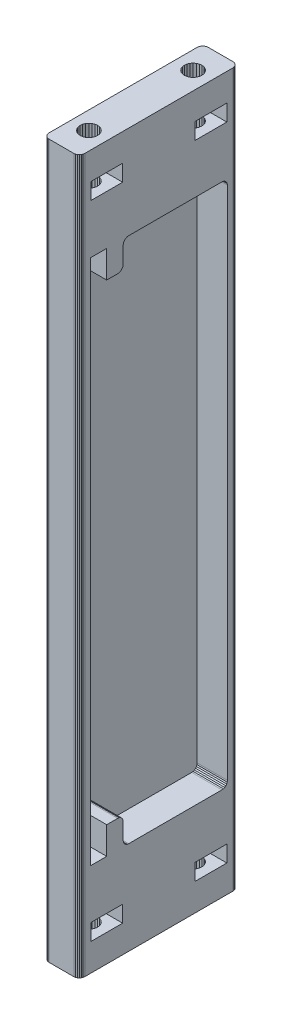
SolidWorks part; units mm, degrees
ref_plane "Front Plane" through (0, 0, 0) normal (0, 0, 1) x (1, 0, 0)
ref_plane "Top Plane" through (0, 0, 0) normal (0, 1, 0) x (1, 0, 0)
ref_plane "Right Plane" through (0, 0, 0) normal (1, 0, 0) x (0, 0, -1)
ref_plane "Plane1" through (0, 130, 0) normal (0, 1, 0) x (1, 0, 0)
sketch "Sketch1" plane through (0, 130, 0) normal (0, 1, 0) x (1, 0, 0)
  line L0 (-2.75, 35.134) -> (-2.5088, 35.0341)
  line L1 (-2.5088, 35.0341) -> (-2.25, 35)
  line L2 (-2.25, 35) -> (2.25, 35)
  line L3 (2.25, 35) -> (2.5088, 35.0341)
  line L4 (2.5088, 35.0341) -> (2.75, 35.134)
  line L5 (2.75, 35.134) -> (2.9571, 35.2929)
  line L6 (2.9571, 35.2929) -> (3.116, 35.5)
  line L7 (3.116, 35.5) -> (3.2159, 35.7412)
  line L8 (3.2159, 35.7412) -> (3.25, 36)
  line L9 (3.25, 36) -> (3.25, 63)
  line L10 (3.25, 63) -> (3.2159, 63.2588)
  line L11 (3.2159, 63.2588) -> (3.116, 63.5)
  line L12 (3.116, 63.5) -> (2.9571, 63.7071)
  line L13 (2.9571, 63.7071) -> (2.75, 63.866)
  line L14 (2.75, 63.866) -> (2.5088, 63.9659)
  line L15 (2.5088, 63.9659) -> (2.25, 64)
  line L16 (2.25, 64) -> (-2.25, 64)
  line L17 (-2.25, 64) -> (-2.5088, 63.9659)
  line L18 (-2.5088, 63.9659) -> (-2.75, 63.866)
  line L19 (-2.75, 63.866) -> (-2.9571, 63.7071)
  line L20 (-2.9571, 63.7071) -> (-3.116, 63.5)
  line L21 (-3.116, 63.5) -> (-3.2159, 63.2588)
  line L22 (-3.2159, 63.2588) -> (-3.25, 63)
  line L23 (-3.25, 63) -> (-3.25, 36)
  line L24 (-3.25, 36) -> (-3.2159, 35.7412)
  line L25 (-3.2159, 35.7412) -> (-3.116, 35.5)
  line L26 (-3.116, 35.5) -> (-2.9571, 35.2929)
  line L27 (-2.9571, 35.2929) -> (-2.75, 35.134)
extrude "Boss-Extrude1" add sketch "Sketch1" against normal blind 130
sketch "Sketch2" plane through (3.25, 0, 0) normal (1, 0, 0) x (0, 0, -1)
  line L0 (37.1, 8) -> (37.1, 5)
  line L1 (37.1, 5) -> (42.9, 5)
  line L2 (42.9, 5) -> (42.9, 8)
  line L3 (42.9, 8) -> (37.1, 8)
extrude "Cut-Extrude1" cut sketch "Sketch2" against normal through all
sketch "Sketch3" plane through (0, 0, 0) normal (0, -1, 0) x (1, 0, 0)
  line L0 (-1.5455, -40.4141) -> (-1.3856, -40.8)
  line L1 (-1.3856, -40.8) -> (-1.1314, -41.1314)
  line L2 (-1.1314, -41.1314) -> (-0.8, -41.3856)
  line L3 (-0.8, -41.3856) -> (-0.4141, -41.5455)
  line L4 (-0.4141, -41.5455) -> (0, -41.6)
  line L5 (0, -41.6) -> (0.4141, -41.5455)
  line L6 (0.4141, -41.5455) -> (0.8, -41.3856)
  line L7 (0.8, -41.3856) -> (1.1314, -41.1314)
  line L8 (1.1314, -41.1314) -> (1.3856, -40.8)
  line L9 (1.3856, -40.8) -> (1.5455, -40.4141)
  line L10 (1.5455, -40.4141) -> (1.6, -40)
  line L11 (1.6, -40) -> (1.5455, -39.5859)
  line L12 (1.5455, -39.5859) -> (1.3856, -39.2)
  line L13 (1.3856, -39.2) -> (1.1314, -38.8686)
  line L14 (1.1314, -38.8686) -> (0.8, -38.6144)
  line L15 (0.8, -38.6144) -> (0.4141, -38.4545)
  line L16 (0.4141, -38.4545) -> (0, -38.4)
  line L17 (0, -38.4) -> (-0.4141, -38.4545)
  line L18 (-0.4141, -38.4545) -> (-0.8, -38.6144)
  line L19 (-0.8, -38.6144) -> (-1.1314, -38.8686)
  line L20 (-1.1314, -38.8686) -> (-1.3856, -39.2)
  line L21 (-1.3856, -39.2) -> (-1.5455, -39.5859)
  line L22 (-1.5455, -39.5859) -> (-1.6, -40)
  line L23 (-1.6, -40) -> (-1.5455, -40.4141)
extrude "Cut-Extrude2" cut sketch "Sketch3" against normal up to next
sketch "Sketch4" plane through (3.25, 0, 0) normal (1, 0, 0) x (0, 0, -1)
  line L0 (37.1, 125) -> (37.1, 122)
  line L1 (37.1, 122) -> (42.9, 122)
  line L2 (42.9, 122) -> (42.9, 125)
  line L3 (42.9, 125) -> (37.1, 125)
extrude "Cut-Extrude3" cut sketch "Sketch4" against normal through all
sketch "Sketch5" plane through (3.25, 0, 0) normal (1, 0, 0) x (0, 0, -1)
  line L0 (61.9, 125) -> (56.1, 125)
  line L1 (56.1, 125) -> (56.1, 122)
  line L2 (56.1, 122) -> (61.9, 122)
  line L3 (61.9, 122) -> (61.9, 125)
extrude "Cut-Extrude4" cut sketch "Sketch5" against normal through all
sketch "Sketch6" plane through (0, 130, 0) normal (0, 1, 0) x (-1, 0, 0)
  line L0 (1.5455, -39.5859) -> (1.3856, -39.2)
  line L1 (1.3856, -39.2) -> (1.1314, -38.8686)
  line L2 (1.1314, -38.8686) -> (0.8, -38.6144)
  line L3 (0.8, -38.6144) -> (0.4141, -38.4545)
  line L4 (0.4141, -38.4545) -> (0, -38.4)
  line L5 (0, -38.4) -> (-0.4141, -38.4545)
  line L6 (-0.4141, -38.4545) -> (-0.8, -38.6144)
  line L7 (-0.8, -38.6144) -> (-1.1314, -38.8686)
  line L8 (-1.1314, -38.8686) -> (-1.3856, -39.2)
  line L9 (-1.3856, -39.2) -> (-1.5455, -39.5859)
  line L10 (-1.5455, -39.5859) -> (-1.6, -40)
  line L11 (-1.6, -40) -> (-1.5455, -40.4141)
  line L12 (-1.5455, -40.4141) -> (-1.3856, -40.8)
  line L13 (-1.3856, -40.8) -> (-1.1314, -41.1314)
  line L14 (-1.1314, -41.1314) -> (-0.8, -41.3856)
  line L15 (-0.8, -41.3856) -> (-0.4141, -41.5455)
  line L16 (-0.4141, -41.5455) -> (0, -41.6)
  line L17 (0, -41.6) -> (0.4141, -41.5455)
  line L18 (0.4141, -41.5455) -> (0.8, -41.3856)
  line L19 (0.8, -41.3856) -> (1.1314, -41.1314)
  line L20 (1.1314, -41.1314) -> (1.3856, -40.8)
  line L21 (1.3856, -40.8) -> (1.5455, -40.4141)
  line L22 (1.5455, -40.4141) -> (1.6, -40)
  line L23 (1.6, -40) -> (1.5455, -39.5859)
extrude "Cut-Extrude5" cut sketch "Sketch6" against normal up to next
sketch "Sketch7" plane through (0, 130, 0) normal (0, 1, 0) x (-1, 0, 0)
  line L0 (-1.6, -59) -> (-1.5455, -59.4141)
  line L1 (-1.5455, -59.4141) -> (-1.3856, -59.8)
  line L2 (-1.3856, -59.8) -> (-1.1314, -60.1314)
  line L3 (-1.1314, -60.1314) -> (-0.8, -60.3856)
  line L4 (-0.8, -60.3856) -> (-0.4141, -60.5455)
  line L5 (-0.4141, -60.5455) -> (0, -60.6)
  line L6 (0, -60.6) -> (0.4141, -60.5455)
  line L7 (0.4141, -60.5455) -> (0.8, -60.3856)
  line L8 (0.8, -60.3856) -> (1.1314, -60.1314)
  line L9 (1.1314, -60.1314) -> (1.3856, -59.8)
  line L10 (1.3856, -59.8) -> (1.5455, -59.4141)
  line L11 (1.5455, -59.4141) -> (1.6, -59)
  line L12 (1.6, -59) -> (1.5455, -58.5859)
  line L13 (1.5455, -58.5859) -> (1.3856, -58.2)
  line L14 (1.3856, -58.2) -> (1.1314, -57.8686)
  line L15 (1.1314, -57.8686) -> (0.8, -57.6144)
  line L16 (0.8, -57.6144) -> (0.4141, -57.4545)
  line L17 (0.4141, -57.4545) -> (0, -57.4)
  line L18 (0, -57.4) -> (-0.4141, -57.4545)
  line L19 (-0.4141, -57.4545) -> (-0.8, -57.6144)
  line L20 (-0.8, -57.6144) -> (-1.1314, -57.8686)
  line L21 (-1.1314, -57.8686) -> (-1.3856, -58.2)
  line L22 (-1.3856, -58.2) -> (-1.5455, -58.5859)
  line L23 (-1.5455, -58.5859) -> (-1.6, -59)
extrude "Cut-Extrude6" cut sketch "Sketch7" against normal up to next
sketch "Sketch8" plane through (3.25, 0, 0) normal (1, 0, 0) x (0, 0, -1)
  line L0 (56.1, 8) -> (56.1, 5)
  line L1 (56.1, 5) -> (61.9, 5)
  line L2 (61.9, 5) -> (61.9, 8)
  line L3 (61.9, 8) -> (56.1, 8)
extrude "Cut-Extrude7" cut sketch "Sketch8" against normal through all
sketch "Sketch9" plane through (0, 0, 0) normal (0, -1, 0) x (1, 0, 0)
  line L0 (-0.8, -57.6144) -> (-1.1314, -57.8686)
  line L1 (-1.1314, -57.8686) -> (-1.3856, -58.2)
  line L2 (-1.3856, -58.2) -> (-1.5455, -58.5859)
  line L3 (-1.5455, -58.5859) -> (-1.6, -59)
  line L4 (-1.6, -59) -> (-1.5455, -59.4141)
  line L5 (-1.5455, -59.4141) -> (-1.3856, -59.8)
  line L6 (-1.3856, -59.8) -> (-1.1314, -60.1314)
  line L7 (-1.1314, -60.1314) -> (-0.8, -60.3856)
  line L8 (-0.8, -60.3856) -> (-0.4141, -60.5455)
  line L9 (-0.4141, -60.5455) -> (0, -60.6)
  line L10 (0, -60.6) -> (0.4141, -60.5455)
  line L11 (0.4141, -60.5455) -> (0.8, -60.3856)
  line L12 (0.8, -60.3856) -> (1.1314, -60.1314)
  line L13 (1.1314, -60.1314) -> (1.3856, -59.8)
  line L14 (1.3856, -59.8) -> (1.5455, -59.4141)
  line L15 (1.5455, -59.4141) -> (1.6, -59)
  line L16 (1.6, -59) -> (1.5455, -58.5859)
  line L17 (1.5455, -58.5859) -> (1.3856, -58.2)
  line L18 (1.3856, -58.2) -> (1.1314, -57.8686)
  line L19 (1.1314, -57.8686) -> (0.8, -57.6144)
  line L20 (0.8, -57.6144) -> (0.4141, -57.4545)
  line L21 (0.4141, -57.4545) -> (0, -57.4)
  line L22 (0, -57.4) -> (-0.4141, -57.4545)
  line L23 (-0.4141, -57.4545) -> (-0.8, -57.6144)
extrude "Cut-Extrude8" cut sketch "Sketch9" against normal up to next
sketch "Sketch10" plane through (3.25, 0, 0) normal (1, 0, 0) x (0, 0, -1)
  line L0 (62, 18) -> (62, 112)
  line L1 (62, 112) -> (61.9659, 112.2588)
  line L2 (61.9659, 112.2588) -> (61.866, 112.5)
  line L3 (61.866, 112.5) -> (61.7071, 112.7071)
  line L4 (61.7071, 112.7071) -> (61.5, 112.866)
  line L5 (61.5, 112.866) -> (61.2588, 112.9659)
  line L6 (61.2588, 112.9659) -> (61, 113)
  line L7 (61, 113) -> (44, 113)
  line L8 (44, 113) -> (43.7412, 112.9659)
  line L9 (43.7412, 112.9659) -> (43.5, 112.866)
  line L10 (43.5, 112.866) -> (43.2929, 112.7071)
  line L11 (43.2929, 112.7071) -> (43.134, 112.5)
  line L12 (43.134, 112.5) -> (43.0341, 112.2588)
  line L13 (43.0341, 112.2588) -> (43, 112)
  line L14 (43, 112) -> (43, 109)
  line L15 (43, 109) -> (42.9659, 108.7412)
  line L16 (42.9659, 108.7412) -> (42.866, 108.5)
  line L17 (42.866, 108.5) -> (42.7071, 108.2929)
  line L18 (42.7071, 108.2929) -> (42.5, 108.134)
  line L19 (42.5, 108.134) -> (42.2588, 108.0341)
  line L20 (42.2588, 108.0341) -> (42, 108)
  line L21 (42, 108) -> (40, 108)
  line L22 (40, 108) -> (40, 113)
  line L23 (40, 113) -> (37, 113)
  line L24 (37, 113) -> (37, 17)
  line L25 (37, 17) -> (40, 17)
  line L26 (40, 17) -> (40, 22)
  line L27 (40, 22) -> (42, 22)
  line L28 (42, 22) -> (42.2588, 21.9659)
  line L29 (42.2588, 21.9659) -> (42.5, 21.866)
  line L30 (42.5, 21.866) -> (42.7071, 21.7071)
  line L31 (42.7071, 21.7071) -> (42.866, 21.5)
  line L32 (42.866, 21.5) -> (42.9659, 21.2588)
  line L33 (42.9659, 21.2588) -> (43, 21)
  line L34 (43, 21) -> (43, 18)
  line L35 (43, 18) -> (43.0341, 17.7412)
  line L36 (43.0341, 17.7412) -> (43.134, 17.5)
  line L37 (43.134, 17.5) -> (43.2929, 17.2929)
  line L38 (43.2929, 17.2929) -> (43.5, 17.134)
  line L39 (43.5, 17.134) -> (43.7412, 17.0341)
  line L40 (43.7412, 17.0341) -> (44, 17)
  line L41 (44, 17) -> (61, 17)
  line L42 (61, 17) -> (61.2588, 17.0341)
  line L43 (61.2588, 17.0341) -> (61.5, 17.134)
  line L44 (61.5, 17.134) -> (61.7071, 17.2929)
  line L45 (61.7071, 17.2929) -> (61.866, 17.5)
  line L46 (61.866, 17.5) -> (61.9659, 17.7412)
  line L47 (61.9659, 17.7412) -> (62, 18)
extrude "Cut-Extrude9" cut sketch "Sketch10" against normal blind 5.5
sketch "Sketch11" plane through (0, 122, 0) normal (0, 1, 0) x (-1, 0, 0)
  line L0 (1.5455, -40.4141) -> (1.6, -40)
  line L1 (1.6, -40) -> (1.5455, -39.5859)
  line L2 (1.5455, -39.5859) -> (1.3856, -39.2)
  line L3 (1.3856, -39.2) -> (1.1314, -38.8686)
  line L4 (1.1314, -38.8686) -> (0.8, -38.6144)
  line L5 (0.8, -38.6144) -> (0.4141, -38.4545)
  line L6 (0.4141, -38.4545) -> (0, -38.4)
  line L7 (0, -38.4) -> (-0.4141, -38.4545)
  line L8 (-0.4141, -38.4545) -> (-0.8, -38.6144)
  line L9 (-0.8, -38.6144) -> (-1.1314, -38.8686)
  line L10 (-1.1314, -38.8686) -> (-1.3856, -39.2)
  line L11 (-1.3856, -39.2) -> (-1.5455, -39.5859)
  line L12 (-1.5455, -39.5859) -> (-1.6, -40)
  line L13 (-1.6, -40) -> (-1.5455, -40.4141)
  line L14 (-1.5455, -40.4141) -> (-1.3856, -40.8)
  line L15 (-1.3856, -40.8) -> (-1.1314, -41.1314)
  line L16 (-1.1314, -41.1314) -> (-0.8, -41.3856)
  line L17 (-0.8, -41.3856) -> (-0.4141, -41.5455)
  line L18 (-0.4141, -41.5455) -> (0, -41.6)
  line L19 (0, -41.6) -> (0.4141, -41.5455)
  line L20 (0.4141, -41.5455) -> (0.8, -41.3856)
  line L21 (0.8, -41.3856) -> (1.1314, -41.1314)
  line L22 (1.1314, -41.1314) -> (1.3856, -40.8)
  line L23 (1.3856, -40.8) -> (1.5455, -40.4141)
extrude "Cut-Extrude10" cut sketch "Sketch11" against normal blind 7
sketch "Sketch12" plane through (0, 122, 0) normal (0, 1, 0) x (-1, 0, 0)
  line L0 (1.5455, -59.4141) -> (1.6, -59)
  line L1 (1.6, -59) -> (1.5455, -58.5859)
  line L2 (1.5455, -58.5859) -> (1.3856, -58.2)
  line L3 (1.3856, -58.2) -> (1.1314, -57.8686)
  line L4 (1.1314, -57.8686) -> (0.8, -57.6144)
  line L5 (0.8, -57.6144) -> (0.4141, -57.4545)
  line L6 (0.4141, -57.4545) -> (0, -57.4)
  line L7 (0, -57.4) -> (-0.4141, -57.4545)
  line L8 (-0.4141, -57.4545) -> (-0.8, -57.6144)
  line L9 (-0.8, -57.6144) -> (-1.1314, -57.8686)
  line L10 (-1.1314, -57.8686) -> (-1.3856, -58.2)
  line L11 (-1.3856, -58.2) -> (-1.5455, -58.5859)
  line L12 (-1.5455, -58.5859) -> (-1.6, -59)
  line L13 (-1.6, -59) -> (-1.5455, -59.4141)
  line L14 (-1.5455, -59.4141) -> (-1.3856, -59.8)
  line L15 (-1.3856, -59.8) -> (-1.1314, -60.1314)
  line L16 (-1.1314, -60.1314) -> (-0.8, -60.3856)
  line L17 (-0.8, -60.3856) -> (-0.4141, -60.5455)
  line L18 (-0.4141, -60.5455) -> (0, -60.6)
  line L19 (0, -60.6) -> (0.4141, -60.5455)
  line L20 (0.4141, -60.5455) -> (0.8, -60.3856)
  line L21 (0.8, -60.3856) -> (1.1314, -60.1314)
  line L22 (1.1314, -60.1314) -> (1.3856, -59.8)
  line L23 (1.3856, -59.8) -> (1.5455, -59.4141)
extrude "Cut-Extrude11" cut sketch "Sketch12" against normal blind 7
sketch "Sketch13" plane through (0, 8, 0) normal (0, -1, 0) x (1, 0, 0)
  line L0 (-0.4141, -41.5455) -> (0, -41.6)
  line L1 (0, -41.6) -> (0.4141, -41.5455)
  line L2 (0.4141, -41.5455) -> (0.8, -41.3856)
  line L3 (0.8, -41.3856) -> (1.1314, -41.1314)
  line L4 (1.1314, -41.1314) -> (1.3856, -40.8)
  line L5 (1.3856, -40.8) -> (1.5455, -40.4141)
  line L6 (1.5455, -40.4141) -> (1.6, -40)
  line L7 (1.6, -40) -> (1.5455, -39.5859)
  line L8 (1.5455, -39.5859) -> (1.3856, -39.2)
  line L9 (1.3856, -39.2) -> (1.1314, -38.8686)
  line L10 (1.1314, -38.8686) -> (0.8, -38.6144)
  line L11 (0.8, -38.6144) -> (0.4141, -38.4545)
  line L12 (0.4141, -38.4545) -> (0, -38.4)
  line L13 (0, -38.4) -> (-0.4141, -38.4545)
  line L14 (-0.4141, -38.4545) -> (-0.8, -38.6144)
  line L15 (-0.8, -38.6144) -> (-1.1314, -38.8686)
  line L16 (-1.1314, -38.8686) -> (-1.3856, -39.2)
  line L17 (-1.3856, -39.2) -> (-1.5455, -39.5859)
  line L18 (-1.5455, -39.5859) -> (-1.6, -40)
  line L19 (-1.6, -40) -> (-1.5455, -40.4141)
  line L20 (-1.5455, -40.4141) -> (-1.3856, -40.8)
  line L21 (-1.3856, -40.8) -> (-1.1314, -41.1314)
  line L22 (-1.1314, -41.1314) -> (-0.8, -41.3856)
  line L23 (-0.8, -41.3856) -> (-0.4141, -41.5455)
extrude "Cut-Extrude12" cut sketch "Sketch13" against normal blind 7
sketch "Sketch14" plane through (0, 8, 0) normal (0, -1, 0) x (1, 0, 0)
  line L0 (-0.4141, -60.5455) -> (0, -60.6)
  line L1 (0, -60.6) -> (0.4141, -60.5455)
  line L2 (0.4141, -60.5455) -> (0.8, -60.3856)
  line L3 (0.8, -60.3856) -> (1.1314, -60.1314)
  line L4 (1.1314, -60.1314) -> (1.3856, -59.8)
  line L5 (1.3856, -59.8) -> (1.5455, -59.4141)
  line L6 (1.5455, -59.4141) -> (1.6, -59)
  line L7 (1.6, -59) -> (1.5455, -58.5859)
  line L8 (1.5455, -58.5859) -> (1.3856, -58.2)
  line L9 (1.3856, -58.2) -> (1.1314, -57.8686)
  line L10 (1.1314, -57.8686) -> (0.8, -57.6144)
  line L11 (0.8, -57.6144) -> (0.4141, -57.4545)
  line L12 (0.4141, -57.4545) -> (0, -57.4)
  line L13 (0, -57.4) -> (-0.4141, -57.4545)
  line L14 (-0.4141, -57.4545) -> (-0.8, -57.6144)
  line L15 (-0.8, -57.6144) -> (-1.1314, -57.8686)
  line L16 (-1.1314, -57.8686) -> (-1.3856, -58.2)
  line L17 (-1.3856, -58.2) -> (-1.5455, -58.5859)
  line L18 (-1.5455, -58.5859) -> (-1.6, -59)
  line L19 (-1.6, -59) -> (-1.5455, -59.4141)
  line L20 (-1.5455, -59.4141) -> (-1.3856, -59.8)
  line L21 (-1.3856, -59.8) -> (-1.1314, -60.1314)
  line L22 (-1.1314, -60.1314) -> (-0.8, -60.3856)
  line L23 (-0.8, -60.3856) -> (-0.4141, -60.5455)
extrude "Cut-Extrude13" cut sketch "Sketch14" against normal blind 7
